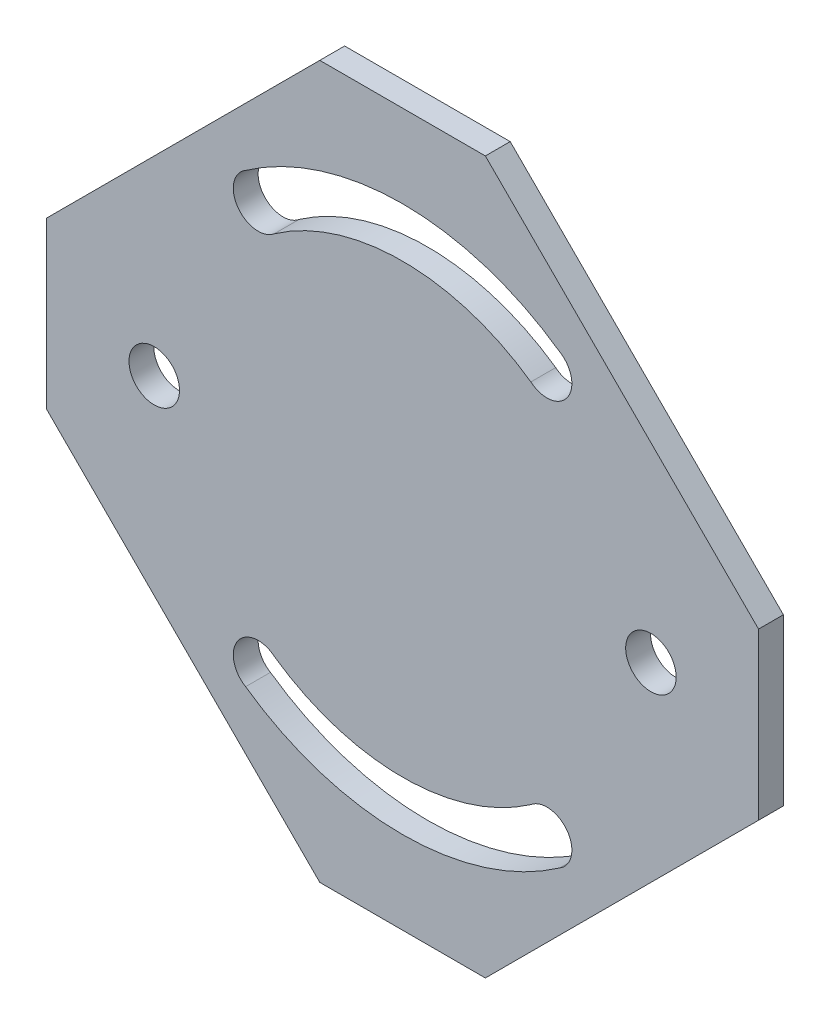
SolidWorks part; units mm, degrees
ref_plane "前视基准面" through (0, 0, 0) normal (0, 0, 1) x (1, 0, 0)
ref_plane "上视基准面" through (0, 0, 0) normal (0, 1, 0) x (1, 0, 0)
ref_plane "右视基准面" through (0, 0, 0) normal (1, 0, 0) x (0, 0, -1)
sketch "草图1" plane through (0, 0, 0) normal (0, 0, 1) x (1, 0, 0)
  line L0 (43.039, -10.4453) -> (43.039, 9.5544)
  line L1 (-42.9596, -10.4453) -> (-42.9596, 9.5544)
  line L2 (10.0396, -43.4448) -> (-9.9601, -43.4448)
  line L3 (10.0396, 42.5539) -> (-9.9601, 42.5539)
  line L4 (10.0396, -43.4448) -> (43.039, -10.4453)
  line L5 (-9.9601, -43.4448) -> (-42.9596, -10.4453)
  line L6 (10.0396, 42.5539) -> (43.039, 9.5544)
  line L7 (-9.9601, 42.5539) -> (-42.9596, 9.5544)
  arc A0 (15.5369, 21.6637) -> (-15.4574, 21.6637) centre (0.0397, -0.4455) ccw
  arc A1 (19.0039, 26.5606) -> (-18.9244, 26.5606) centre (0.0397, -0.4455) ccw
  circle A2 centre (30.0393, -0.4455) radius 3.05
  circle A3 centre (-29.9598, -0.4455) radius 3.05
  arc A4 (-15.4574, -22.5546) -> (15.5369, -22.5546) centre (0.0397, -0.4455) ccw
  arc A5 (-18.9244, -27.4515) -> (19.0039, -27.4515) centre (0.0397, -0.4455) ccw
  arc A6 (15.5369, 21.6637) -> (19.0039, 26.5606) centre (17.4791, 23.9643) ccw
  arc A7 (-18.9244, 26.5606) -> (-15.4574, 21.6637) centre (-17.3997, 23.9643) ccw
  arc A8 (19.0039, -27.4515) -> (15.5369, -22.5546) centre (17.4791, -24.8553) ccw
  arc A9 (-15.4574, -22.5546) -> (-18.9244, -27.4515) centre (-17.3997, -24.8553) ccw
extrude "凸台-拉伸1" add sketch "草图1" along normal blind 3
